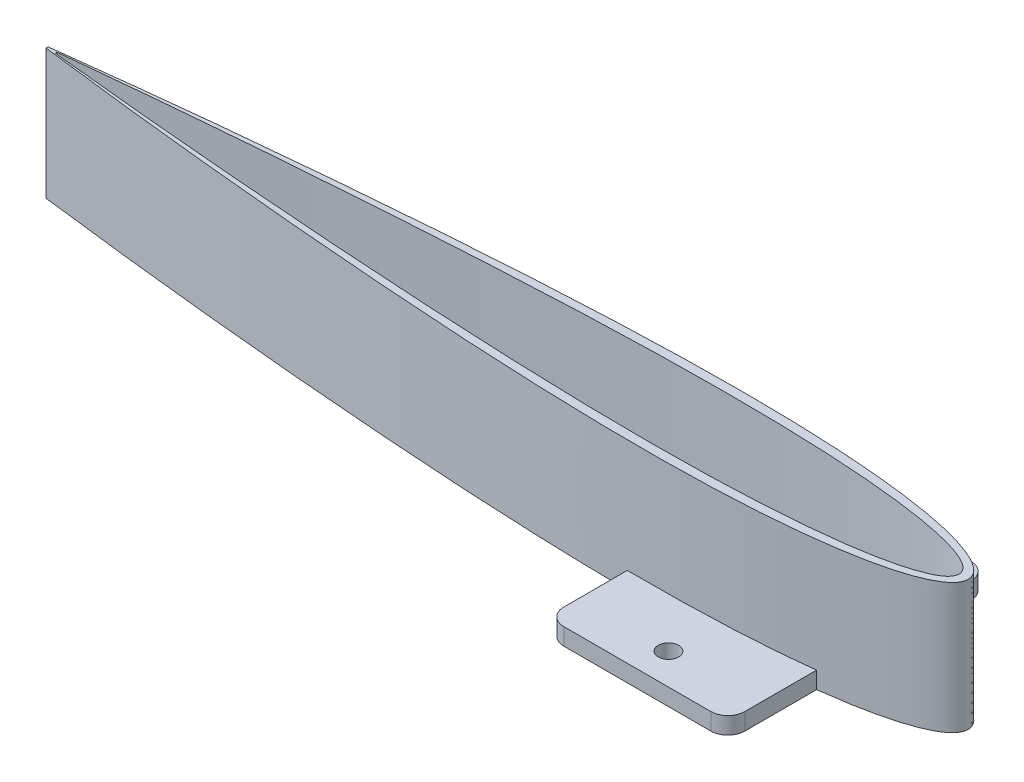
SolidWorks part; units mm, degrees
ref_plane "Front Plane" through (0, 0, 0) normal (0, 0, 1) x (1, 0, 0)
ref_plane "Top Plane" through (0, 0, 0) normal (0, 1, 0) x (1, 0, 0)
ref_plane "Right Plane" through (0, 0, 0) normal (1, 0, 0) x (0, 0, -1)
sketch "Sketch1" plane through (0, 0, 0) normal (0, 1, 0) x (1, 0, 0)
  line L0 (-161.284, 0.1845) -> (-161.284, -0.1845)
  spline S0 degree 3 poles (-161.284, 0.1845) (-161.1353, 0.2032) (-160.5421, 0.278) (-159.2135, 0.4441) (-157.0155, 0.7154) (-153.9719, 1.0837) (-150.1161, 1.5386) (-145.4905, 2.0678) (-140.1455, 2.6577) (-134.1398, 3.2942) (-127.5393, 3.9626) (-120.4161, 4.648) (-112.8485, 5.3351) (-104.9192, 6.0078) (-96.7152, 6.6493) (-88.3264, 7.2417) (-79.8445, 7.7664) (-71.3624, 8.2042) (-62.973, 8.5362) (-54.7681, 8.7444) (-46.8374, 8.8135) (-39.2678, 8.7313) (-32.142, 8.4902) (-25.5378, 8.0881) (-19.5272, 7.5283) (-14.1754, 6.8193) (-9.5387, 5.9752) (-5.6663, 5.0117) (-2.5865, 3.9511) (-0.3254, 2.7972) (1.1775, 1.5494) (1.7831, 0) (1.1775, -1.5494) (-0.3254, -2.7972) (-2.5865, -3.9511) (-5.6663, -5.0117) (-9.5387, -5.9752) (-14.1754, -6.8193) (-19.5272, -7.5283) (-25.5378, -8.0881) (-32.142, -8.4902) (-39.2678, -8.7313) (-46.8374, -8.8135) (-54.7681, -8.7444) (-62.973, -8.5362) (-71.3624, -8.2042) (-79.8445, -7.7664) (-88.3264, -7.2417) (-96.7152, -6.6493) (-104.9192, -6.0078) (-112.8485, -5.3351) (-120.4161, -4.648) (-127.5393, -3.9626) (-134.1398, -3.2942) (-140.1455, -2.6577) (-145.4905, -2.0678) (-150.1161, -1.5386) (-153.9719, -1.0837) (-157.0155, -0.7154) (-159.2135, -0.4441) (-160.5421, -0.278) (-161.1353, -0.2032) (-161.284, -0.1845) knots 0 0 0 0 0.001358 0.005418 0.012133 0.021429 0.0332 0.047316 0.06362 0.08193 0.102044 0.12374 0.146778 0.170904 0.195853 0.221349 0.247113 0.272862 0.298315 0.323195 0.347236 0.370181 0.39179 0.411841 0.430131 0.446483 0.460748 0.472815 0.48262 0.490192 0.495749 0.5 0.504251 0.509808 0.51738 0.527185 0.539252 0.553517 0.569869 0.588159 0.60821 0.629819 0.652764 0.676805 0.701685 0.727138 0.752887 0.778651 0.804147 0.829096 0.853222 0.87626 0.897956 0.91807 0.93638 0.952684 0.9668 0.978571 0.987867 0.994582 0.998642 1 1 1 1
extrude "Boss-Extrude1" add sketch "Sketch1" along normal blind 23
sketch "Sketch2" plane through (0, 0, 0) normal (0, 1, 0) x (1, 0, 0)
  line L0 (-46.9, -23) -> (-20.9, -23)
  line L1 (-17.9, -20) -> (-17.9, 20)
  line L2 (-20.9, 23) -> (-46.9, 23)
  line L3 (-49.9, 20) -> (-49.9, -20)
  arc A0 (-20.9, -23) -> (-17.9, -20) centre (-20.9, -20) ccw
  arc A1 (-17.9, 20) -> (-20.9, 23) centre (-20.9, 20) ccw
  arc A2 (-46.9, 23) -> (-49.9, 20) centre (-46.9, 20) ccw
  arc A3 (-49.9, -20) -> (-46.9, -23) centre (-46.9, -20) ccw
extrude "Boss-Extrude2" add sketch "Sketch2" along normal blind 3
ref_plane "Plane1" through (0, 23, 0) normal (0, 1, 0) x (1, 0, 0)
sketch "Sketch3" plane through (0, 23, 0) normal (0, 1, 0) x (1, 0, 0)
  line L0 (-159.684, 0.1509) -> (-159.684, -0.1509)
  spline S0 degree 3 poles (-159.684, 0.1509) (-159.5382, 0.1662) (-158.9567, 0.2274) (-157.6542, 0.3632) (-155.4992, 0.5851) (-152.5153, 0.8864) (-148.7353, 1.2584) (-144.2004, 1.6912) (-138.9604, 2.1737) (-133.0727, 2.6943) (-126.6017, 3.241) (-119.6185, 3.8016) (-112.1995, 4.3636) (-104.4259, 4.9138) (-96.3831, 5.4384) (-88.159, 5.9229) (-79.8437, 6.3521) (-71.5283, 6.7102) (-63.3039, 6.9816) (-55.2604, 7.152) (-47.4859, 7.2084) (-40.0655, 7.1412) (-33.0804, 6.9441) (-26.607, 6.6153) (-20.7159, 6.1577) (-15.4712, 5.578) (-10.9284, 4.8889) (-7.1371, 4.101) (-4.1251, 3.2414) (-1.9245, 2.2977) (-0.4585, 1.3227) (0.1896, 0) (-0.4585, -1.3227) (-1.9245, -2.2977) (-4.1251, -3.2414) (-7.1371, -4.101) (-10.9284, -4.8889) (-15.4712, -5.578) (-20.7159, -6.1577) (-26.607, -6.6153) (-33.0804, -6.9441) (-40.0655, -7.1412) (-47.4859, -7.2084) (-55.2604, -7.152) (-63.3039, -6.9816) (-71.5283, -6.7102) (-79.8437, -6.3521) (-88.159, -5.9229) (-96.3831, -5.4384) (-104.4259, -4.9138) (-112.1995, -4.3636) (-119.6185, -3.8016) (-126.6017, -3.241) (-133.0727, -2.6943) (-138.9604, -2.1737) (-144.2004, -1.6912) (-148.7353, -1.2584) (-152.5153, -0.8864) (-155.4992, -0.5851) (-157.6542, -0.3632) (-158.9567, -0.2274) (-159.5382, -0.1662) (-159.684, -0.1509) knots 0 0 0 0 0.001361 0.005428 0.012156 0.02147 0.033267 0.047415 0.063758 0.082114 0.102282 0.124039 0.147146 0.171348 0.196379 0.221963 0.247821 0.273669 0.299223 0.324206 0.348349 0.37139 0.393087 0.41321 0.431552 0.447929 0.462182 0.474186 0.48386 0.491199 0.496361 0.5 0.503639 0.508801 0.51614 0.525814 0.537818 0.552071 0.568448 0.58679 0.606913 0.62861 0.651651 0.675794 0.700777 0.726331 0.752179 0.778037 0.803621 0.828652 0.852854 0.875961 0.897718 0.917886 0.936242 0.952585 0.966733 0.97853 0.987844 0.994572 0.998639 1 1 1 1
extrude "Cut-Extrude1" cut sketch "Sketch3" against normal blind 20
sketch "Sketch4" plane through (0, 0, 0) normal (0, 1, 0) x (1, 0, 0)
  circle A0 centre (-33.9, -17.5) radius 1.8
  circle A1 centre (-33.9, 17.5) radius 1.8
extrude "Cut-Extrude2" cut sketch "Sketch4" along normal blind 3
